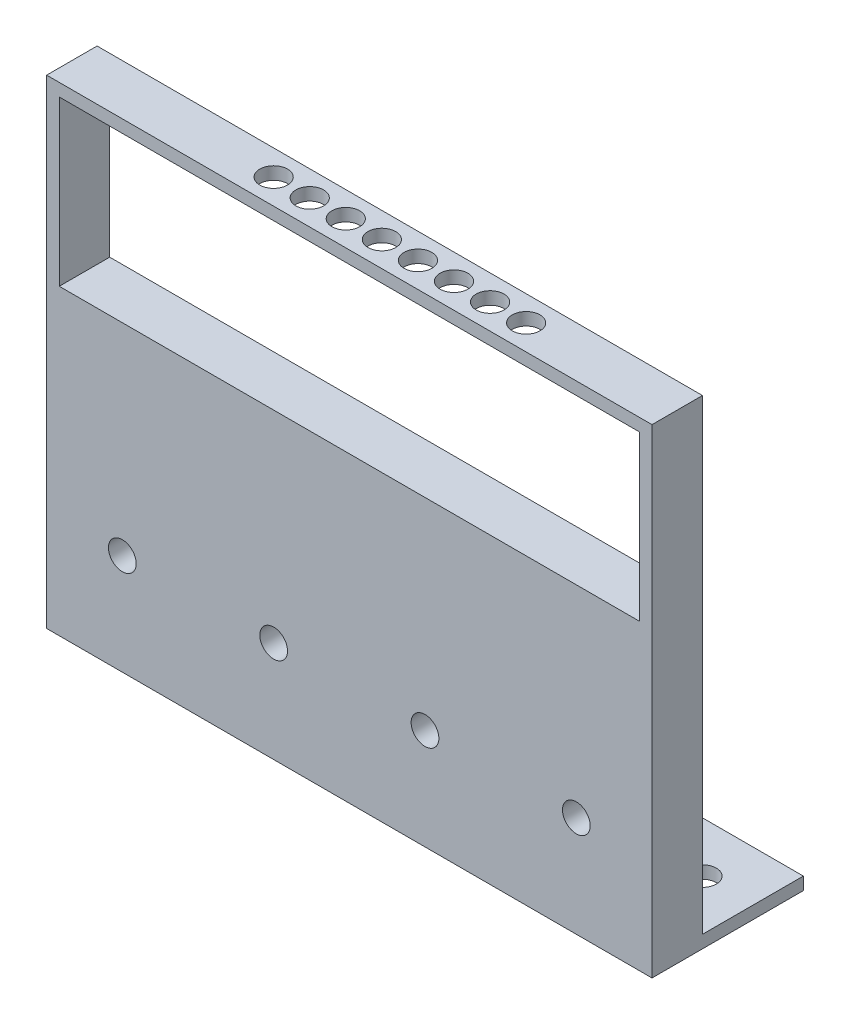
SolidWorks part; units mm, degrees
ref_plane "Front Plane" through (0, 0, 0) normal (0, 0, 1) x (1, 0, 0)
ref_plane "Top Plane" through (0, 0, 0) normal (0, 1, 0) x (1, 0, 0)
ref_plane "Right Plane" through (0, 0, 0) normal (1, 0, 0) x (0, 0, -1)
sketch "Sketch1" plane through (0, 0, 0) normal (0, 1, 0) x (1, 0, 0)
  line L1 (-76.2, -6.35) -> (76.2, -6.35)
  line L2 (-76.2, -6.35) -> (-76.2, 6.35)
  line L3 (-76.2, 6.35) -> (76.2, 6.35)
  line L4 (76.2, -6.35) -> (76.2, 6.35)
  line L5 (-76.2, -6.35) -> (76.2, 6.35) construction
  line L6 (-76.2, 6.35) -> (76.2, -6.35) construction
  point P0 (0, 0)
  dimension "D1" = 12.7
  dimension "D2" = 152.4
extrude "Boss-Extrude1" add sketch "Sketch1" along normal blind 76.2
sketch "Sketch2" plane through (0, 0, 0) normal (0, 1, 0) x (1, 0, 0)
  line L0 (-76.2, 6.35) -> (-76.2, -6.35) construction
  line L1 (-76.2, 19.05) -> (-76.2, 6.35)
  line L2 (-76.2, 6.35) -> (76.2, 6.35)
  line L3 (76.2, 31.75) -> (-76.2, 31.75)
  line L4 (-76.2, 19.05) -> (-76.2, 31.75)
  line L5 (0, 0) -> (-76.2, 31.75) construction
  line L6 (76.2, 31.75) -> (0, 0) construction
  line L7 (76.2, 6.35) -> (-76.2, 6.35) construction
  line L8 (-23.5905, 31.75) -> (-23.5905, 6.35) construction
  line L9 (-23.5905, 19.05) -> (-76.2, 19.05) construction
  line L10 (76.2, 6.35) -> (76.2, 31.75)
  circle A0 centre (-63.5, 19.05) radius 3.4925
  circle A1 centre (-38.1, 19.05) radius 3.4925
  circle A2 centre (-12.7, 19.05) radius 3.4925
  circle A3 centre (12.7, 19.05) radius 3.4925
  circle A4 centre (38.1, 19.05) radius 3.4925
  circle A5 centre (63.5, 19.05) radius 3.4925
  point P0 (0, 0)
  dimension "D2" = 6.985
  dimension "D1" = 25.4
  dimension "D3" = 6
  dimension "D4" = 12.7
extrude "Boss-Extrude4" add sketch "Sketch2" along normal blind 3.175
sketch "Sketch3" plane through (0, 0, 6.35) normal (0, 0, 1) x (1, 0, 0)
  line L0 (-76.2, 76.2) -> (-76.2, 120.65)
  line L1 (-76.2, 120.65) -> (76.2, 120.65)
  line L2 (76.2, 120.65) -> (76.2, 76.2)
  line L3 (76.2, 76.2) -> (76.2, 0) construction
  line L4 (-76.2, 76.2) -> (-76.2, 0) construction
  line L5 (76.2, 76.2) -> (73.025, 76.2)
  line L6 (-76.2, 76.2) -> (76.2, 76.2) construction
  line L7 (73.025, 76.2) -> (73.025, 117.475)
  line L8 (73.025, 117.475) -> (-73.025, 117.475)
  line L9 (-73.025, 117.475) -> (-73.025, 76.2)
  line L10 (-73.025, 76.2) -> (-76.2, 76.2)
  line L11 (-73.025, 117.475) -> (-73.025, 120.65) construction
  dimension "D1" = 3.175
  dimension "D2" = 44.45
extrude "Boss-Extrude5" add sketch "Sketch3" against normal up to surface (12.7 mm away) up to face at (0, 39.6875, -6.35)
sketch "Sketch4" plane through (0, 120.65, 0) normal (0, 1, 0) x (1, 0, 0)
  line L0 (-76.2, 6.35) -> (-76.2, -6.35) construction
  circle A0 centre (-25.4, 0) radius 3.4925
  circle A1 centre (-16.3195, 0) radius 3.4925
  circle A2 centre (-7.239, 0) radius 3.4925
  circle A3 centre (1.8415, 0) radius 3.4925
  circle A4 centre (10.922, 0) radius 3.4925
  circle A5 centre (20.0025, 0) radius 3.4925
  circle A6 centre (29.083, 0) radius 3.4925
  circle A7 centre (38.1635, 0) radius 3.4925
  dimension "D1" = 6.985
  dimension "D2" = 50.8
  dimension "D4" = 9.0805
  dimension "D3" = 8
extrude "Cut-Extrude1" cut sketch "Sketch4" against normal up to next
sketch "Sketch5" plane through (0, 0, 0) normal (0, 0, 1) x (1, 0, 0)
  line L0 (-76.2, 120.65) -> (-76.2, 0) construction
  line L1 (-76.2, 0) -> (76.2, 0) construction
  circle A0 centre (-57.15, 25.4) radius 3.4925
  circle A1 centre (-19.05, 25.4) radius 3.4925
  circle A2 centre (19.05, 25.4) radius 3.4925
  circle A3 centre (57.15, 25.4) radius 3.4925
  dimension "D1" = 6.985
  dimension "D2" = 19.05
  dimension "D3" = 25.4
  dimension "D4" = 4
extrude "Cut-Extrude2" cut sketch "Sketch5" against normal through all both and the other way through all
